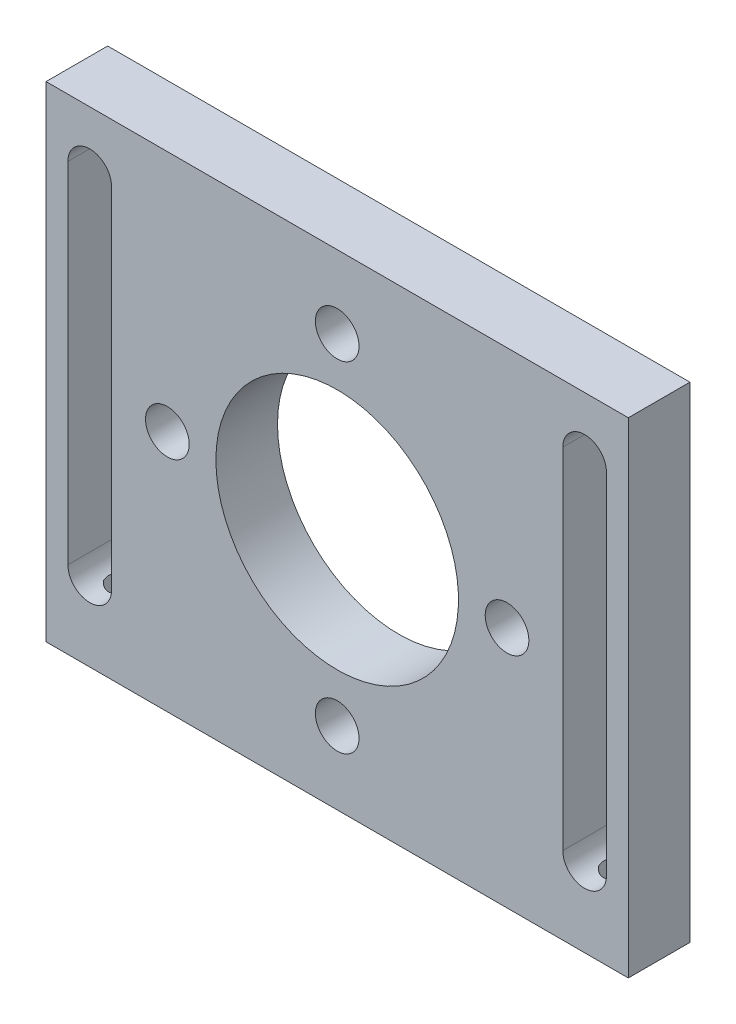
SolidWorks part; units mm, degrees
material "6061 Alloy"
ref_plane "Front" through (0, 0, 0) normal (0, 0, 1) x (1, 0, 0)
ref_plane "Top" through (0, 0, 0) normal (0, 1, 0) x (1, 0, 0)
ref_plane "Right" through (0, 0, 0) normal (1, 0, 0) x (0, 0, -1)
ref_plane "Plane1" through (0, 0, 0) normal (0, 0, -1) x (-1, 0, 0)
sketch "Sketch1" plane through (0, 0, 0) normal (0, 0, -1) x (-1, 0, 0)
  line L0 (30, -25) -> (30, 25)
  line L1 (30, 25) -> (-30, 25)
  line L2 (-30, 25) -> (-30, -25)
  line L3 (-30, -25) -> (30, -25)
  line L4 (0, 25) -> (0, -25) construction
  line L5 (-30, 0) -> (30, 0) construction
  dimension "D1" = 60
  dimension "D2" = 50
extrude "Boss-Extrude1" add sketch "Sketch1" against normal blind 6.35
sketch "Sketch2" plane through (0, 0, 0) normal (0, 0, -1) x (-1, 0, 0)
  line L0 (27.75, -17) -> (27.75, 19)
  line L1 (23.25, 19) -> (23.25, -17)
  line L2 (-30, -25) -> (30, -25) construction
  arc A0 (27.75, 19) -> (23.25, 19) centre (25.5, 19) ccw
  arc A1 (23.25, -17) -> (27.75, -17) centre (25.5, -17) ccw
  dimension "D1" = 2.25
  dimension "D2" = 36
  dimension "D3" = 25.5
  dimension "D4" = 8
extrude "Cut-Extrude1" cut sketch "Sketch2" against normal through all
hole_wizard "Hole1" positions "Sketch5" profile "Sketch4" legacy
sketch "Sketch5" plane through (0, 0, 0) normal (0, 0, -1) x (-1, 0, 0)
  point P0 (0, 0)
sketch "Sketch4" plane through (0, 0, 0) normal (1, 0, 0) x (0, 1, 0)
  line L0 (0, 0) -> (0, 6.35)
  line L1 (0, 6.35) -> (12.5, 6.35)
  line L2 (12.5, 6.35) -> (12.5, 0)
  line L3 (12.5, 0) -> (0, 0)
  line L4 (0, 110) -> (0, -10) construction
  dimension "Diameter" = 25
  dimension "Depth" = 6.35
hole_wizard "CSK for M4 Flat Head Machine Screw1" positions "Sketch7" profile "Sketch6" countersink size "M4" standard "ANSI Metric" end condition through all
sketch "Sketch7" plane through (0, 0, 0) normal (0, 0, -1) x (-1, 0, 0)
  point P0 (0, 17.5)
  point P1 (17.5, 0)
  point P2 (0, -17.5)
  point P3 (-17.5, 0)
sketch "Sketch6" plane through (0, 17.5, 0) normal (1, 0, 0) x (0, 1, 0)
  line L0 (0, 0) -> (0, 6.35)
  line L1 (0, 6.35) -> (2.25, 6.35)
  line L2 (2.25, 6.35) -> (2.25, 2.45)
  line L3 (2.25, 2.45) -> (4.7, 0)
  line L5 (4.7, 0) -> (0, 0)
  line L6 (-2.25, 2.45) -> (-4.7, 0) construction
  line L11 (0, -6.35) -> (0, 107.95) construction
  dimension "Thru Hole Dia." = 4.5
  dimension "Thru Hole Depth" = 6.35
  dimension "Near C'Sink Dia." = 9.4
  dimension "Near C'Sink Angle" = 90
hole_wizard "M3x0.5 Tapped Hole1" positions "Sketch9" profile "Sketch8" tap size "M3x0.5" standard "ANSI Metric"
sketch "Sketch9" plane through (0, -25, 0) normal (0, -1, 0) x (-1, 0, 0)
  point P0 (-25.5, -3.175)
  point P1 (25.5, -3.175)
sketch "Sketch8" plane through (25.5, -25, 3.175) normal (1, 0, 0) x (0, 0, -1)
  line L0 (0, 0) -> (0, 6.7511)
  line L1 (0, 6.7511) -> (1.25, 6)
  line L2 (1.25, 6) -> (1.25, 0)
  line L5 (1.25, 0) -> (0, 0)
  line L10 (0, 6.7511) -> (-1.25, 6) construction
  line L11 (0, -6.35) -> (0, 107.95) construction
  dimension "Tap Drill Dia." = 2.5
  dimension "Tap Drill Depth" = 6
  dimension "Drill Angle" = 118
mirror "Mirror2" about plane through (0, 0, 0) normal (1, 0, 0) of "Cut-Extrude1"
